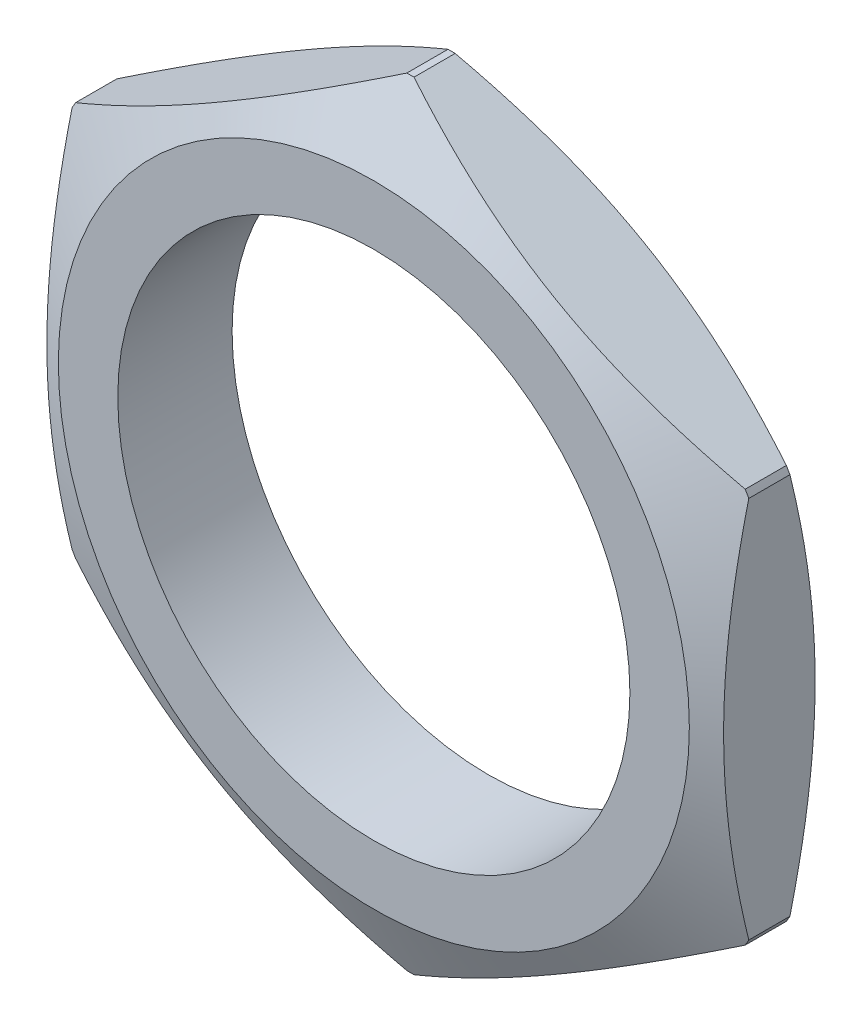
SolidWorks part; units mm, degrees
ref_plane "Спереди" through (0, 0, 0) normal (0, 0, 1) x (1, 0, 0)
ref_plane "Сверху" through (0, 0, 0) normal (0, 1, 0) x (1, 0, 0)
ref_plane "Справа" through (0, 0, 0) normal (1, 0, 0) x (0, 0, -1)
sketch "Эскиз3" plane through (0, 0, 0) normal (0, 0, 1) x (1, 0, 0)
  circle A0 centre (0, 0) radius 8.5
  circle A1 centre (0, 0) radius 5.6
  dimension "D1" = 11.2
  dimension "D2" = 17
extrude "Вытянуть2" add sketch "Эскиз3" along normal blind 2.5
cosmetic thread "Условное изображение резьбы1" parameters "D2"=12
chamfer "Фаска1" distance 0.8 distance2 1.6 1 edges at (8.5, 0, 2.5)
chamfer "Фаска2" distance 1.6 distance2 0.8 1 edges at (8.5, 0, 0)
sketch "Эскиз4" plane through (0, 0, 2.5) normal (0, 0, 1) x (1, 0, 0)
  line L0 (0, 0) -> (0, 13.5061) construction
  line L1 (0, 8.5448) -> (-7.4, 4.2724)
  line L2 (-7.4, 4.2724) -> (-7.4, -4.2724)
  line L3 (-7.4, -4.2724) -> (0, -8.5448)
  line L4 (0, -8.5448) -> (7.4, -4.2724)
  line L5 (7.4, -4.2724) -> (7.4, 4.2724)
  line L6 (7.4, 4.2724) -> (0, 8.5448)
  circle A0 centre (0, 0) radius 7.4 construction
  dimension "D1" = 14.8
extrude "Вытянуть3" cut sketch "Эскиз4" against normal through all flip side to cut
